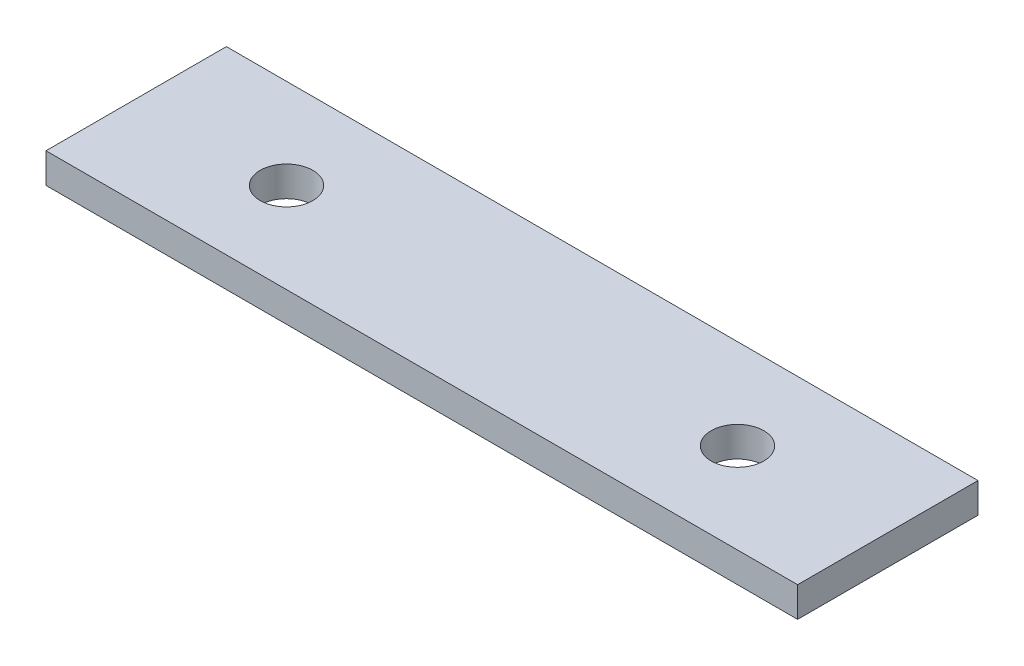
SolidWorks part; units mm, degrees
material "ABS"
ref_plane "Plano frontal" through (0, 0, 0) normal (0, 0, 1) x (1, 0, 0)
ref_plane "Plano superior" through (0, 0, 0) normal (0, 1, 0) x (1, 0, 0)
ref_plane "Plano direito" through (0, 0, 0) normal (1, 0, 0) x (0, 0, -1)
sketch "Esboço1" plane through (0, 0, 0) normal (0, 1, 0) x (1, 0, 0)
  line L1 (25, 6) -> (-25, 6)
  line L2 (25, 6) -> (25, -6)
  line L3 (25, -6) -> (-25, -6)
  line L4 (-25, 6) -> (-25, -6)
  line L5 (25, 6) -> (-25, -6) construction
  line L6 (25, -6) -> (-25, 6) construction
  circle A0 centre (-15, 0) radius 1.75
  circle A1 centre (15, 0) radius 1.75
  point P0 (0, 0)
  point P10 (0, 0)
  point P11 (0, 0)
  dimension "D5" = 3.5
  dimension "D1" = 12
  dimension "D2" = 50
  dimension "D3" = 15
  dimension "D4" = 15
extrude "Ressalto-extrusão1" add sketch "Esboço1" along normal blind 2
equation "\"D4@Esboço1\"=\"D3@Esboço1\""
